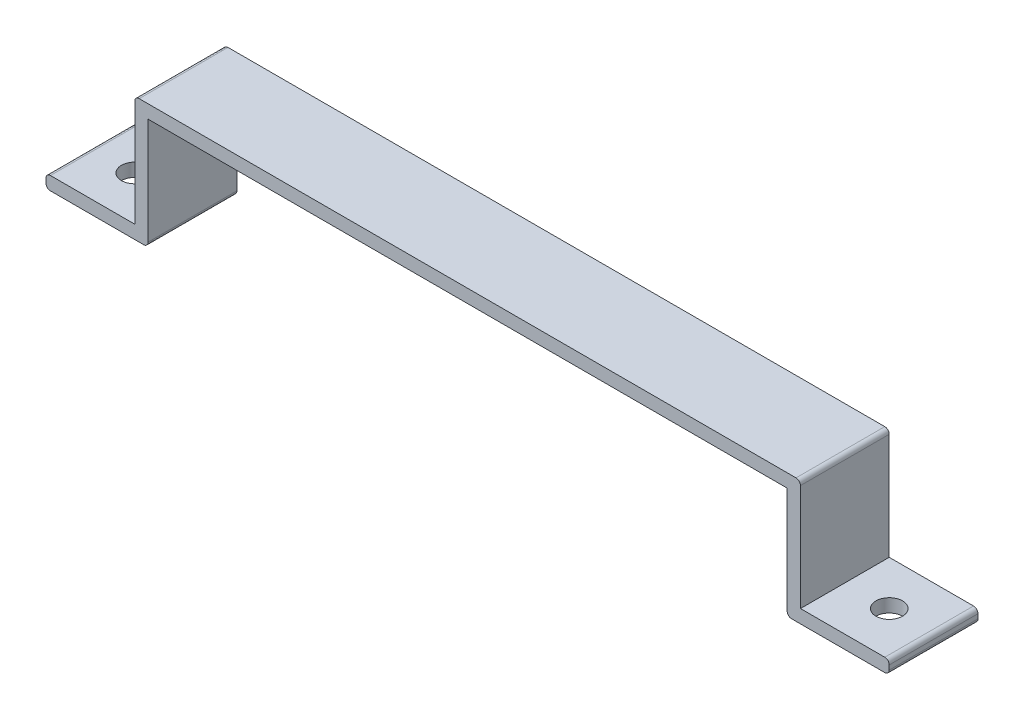
SolidWorks part; units mm, degrees
ref_plane "Front Plane" through (0, 0, 0) normal (0, 0, 1) x (1, 0, 0)
ref_plane "Top Plane" through (0, 0, 0) normal (0, 1, 0) x (1, 0, 0)
ref_plane "Right Plane" through (0, 0, 0) normal (1, 0, 0) x (0, 0, -1)
sketch "Sketch1" plane through (0, 0, 0) normal (0, 0, 1) x (1, 0, 0)
  line L0 (0, 0) -> (20, 0)
  line L1 (20, 0) -> (20, 25)
  line L2 (20, 25) -> (170, 25)
  line L3 (170, 25) -> (170, 0)
  line L4 (170, 0) -> (190, 0)
  dimension "D1" = 150
  dimension "D2" = 25
  dimension "D3" = 20
extrude "Extrude-Thin1" add sketch "Sketch1" along normal blind 20 thin
fillet "Fillet1" radius 1 8 edges at (0, -3, 10) (0, 0, 10) (190, 0, 10) (190, -3, 10) (167, -3, 10) (170, 25, 10) (20, 25, 10) (23, -3, 10)
sketch "Sketch2" plane through (0, 0, 0) normal (0, 1, 0) x (1, 0, 0)
  line L0 (1, 0) -> (20, 0) construction
  line L1 (0, -20) -> (0, 0) construction
  circle A0 centre (10, -10) radius 3
  circle A1 centre (180, -10) radius 3
  dimension "D1" = 6
  dimension "D5" = 170
  dimension "D2" = 10
  dimension "D3" = 10
  dimension "D4" = 2
extrude "Cut-Extrude1" cut sketch "Sketch2" against normal up to next
